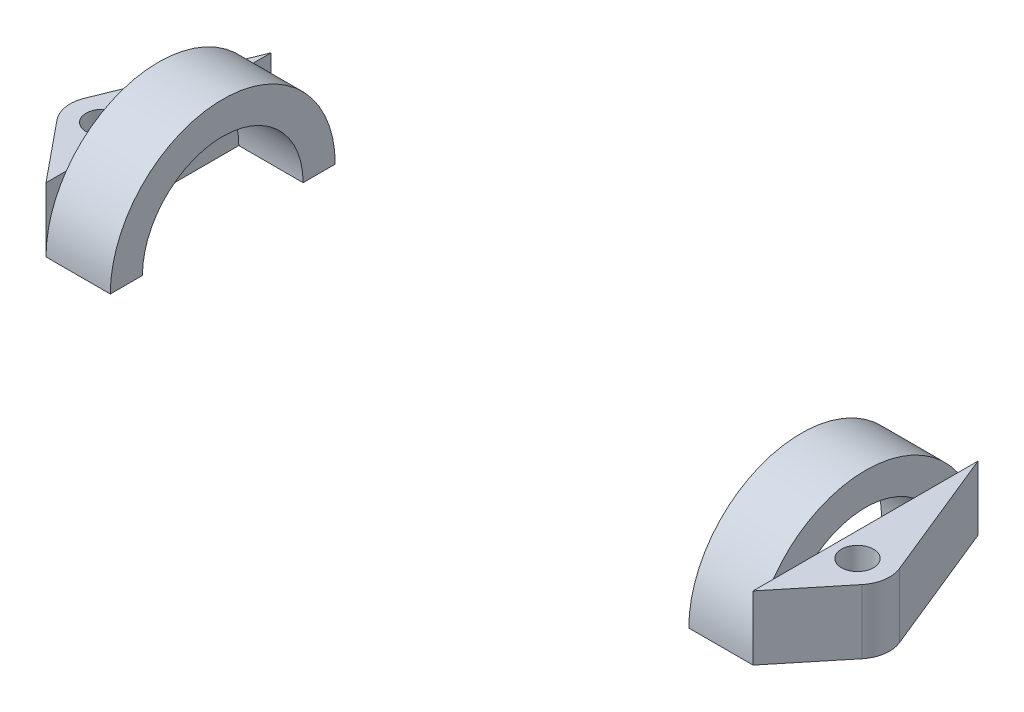
SolidWorks part; units mm, degrees
ref_plane "Front Plane" through (0, 0, 0) normal (0, 0, 1) x (1, 0, 0)
ref_plane "Top Plane" through (0, 0, 0) normal (0, 1, 0) x (1, 0, 0)
ref_plane "Right Plane" through (0, 0, 0) normal (1, 0, 0) x (0, 0, -1)
sketch "Sketch1" plane through (0, 0, 0) normal (1, 0, 0) x (0, 0, -1)
  line L0 (-2.5, 0) -> (2.5, 0)
  line L2 (-2.5, 0) -> (-3.5, 0)
  line L3 (2.5, 0) -> (3.5, 0)
  line L5 (-3.3541, -1) -> (3.3541, -1) construction
  arc A0 (2.5, 0) -> (-2.5, 0) centre (0, 0) ccw
  arc A1 (3.5, 0) -> (-3.5, 0) centre (0, 0) ccw
  arc A3 (3.3541, -1) -> (-3.3541, -1) centre (0, 0) ccw construction
  dimension "D1" = 5
  dimension "D2" = 1
extrude "Boss-Extrude1" add sketch "Sketch1" along normal blind 22 contours L3 A1 L2 A0
sketch "Sketch6" plane through (0, 0, 0) normal (0, 1, 0) x (1, 0, 0)
  line L0 (0, -3.5) -> (0, -1) construction
  line L1 (0, 3.5) -> (0, -3.5) construction
  line L2 (0, -1) -> (-0.75, -1) construction
  line L3 (0, -3.5) -> (-1.5246, -1.6324)
  line L4 (0, -3.5) -> (22, -3.5) construction
  line L5 (22, -3.5) -> (0, -3.5) construction
  line L6 (11, -3.5) -> (11, 10.3583) construction
  line L7 (0, -1) -> (0, 3.5) construction
  line L8 (0, 3.5) -> (-1.6764, -0.6234)
  line L9 (0, 3.5) -> (0, -3.5)
  line L10 (22, 3.5) -> (23.6764, -0.6234)
  line L11 (22, -3.5) -> (23.5246, -1.6324)
  line L12 (22, 3.5) -> (22, -3.5)
  circle A0 centre (-0.75, -1) radius 0.5
  arc A1 (-1.6764, -0.6234) -> (-1.5246, -1.6324) centre (-0.75, -1) ccw
  circle A2 centre (22.75, -1) radius 0.5
  arc A3 (23.6764, -0.6234) -> (23.5246, -1.6324) centre (22.75, -1) cw
  dimension "D2" = 1
  dimension "D4" = 0.5
  dimension "D1" = 0.75
  dimension "D3" = 2.5
  dimension "D5" = 4.5
  dimension "D6" = 22
extrude "Boss-Extrude4" add sketch "Sketch6" along normal blind 2
sketch "Sketch3" plane through (0, 0, 0) normal (0, -1, 0) x (1, 0, 0)
  line L0 (0, 0) -> (22, 0) construction
  line L1 (22, -1.5) -> (22, 1.5) construction
  line L3 (2, 5) -> (20, 5)
  line L4 (2, 5) -> (2, -5)
  line L5 (2, -5) -> (20, -5)
  line L6 (20, 5) -> (20, -5)
  line L7 (2, 5) -> (20, -5) construction
  line L8 (2, -5) -> (20, 5) construction
  point P5 (11, 0)
  dimension "D1" = 2
  dimension "D2" = 10
extrude "Cut-Extrude1" cut sketch "Sketch3" against normal through all
